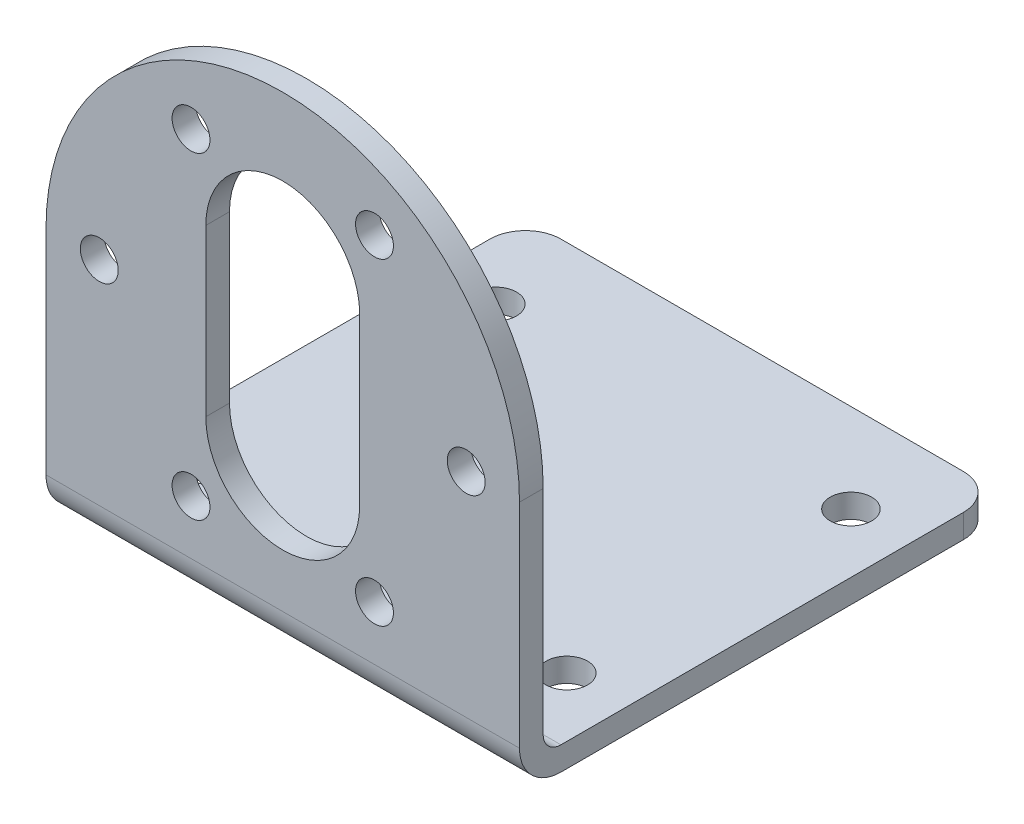
SolidWorks part; units mm, degrees
ref_plane "前视基准面" through (0, 0, 0) normal (0, 0, 1) x (1, 0, 0)
ref_plane "上视基准面" through (0, 0, 0) normal (0, 1, 0) x (1, 0, 0)
ref_plane "右视基准面" through (0, 0, 0) normal (1, 0, 0) x (0, 0, -1)
other "Configuration Table"
ref_plane "基准面1" through (0, 0, 20.25) normal (0, 0, 1) x (1, 0, 0)
sketch "草图1" plane through (0, 0, 20.25) normal (0, 0, 1) x (1, 0, 0)
  line L0 (20, -2) -> (20, 19.5)
  line L1 (-20, 19.5) -> (-20, -2)
  line L2 (-20, -2) -> (20, -2)
  arc A0 (20, 19.5) -> (-20, 19.5) centre (0, 19.5) ccw
extrude "凸台-拉伸1" add sketch "草图1" against normal blind 40.5
sketch "草图2" plane through (20, 0, 0) normal (1, 0, 0) x (0, 0, -1)
  line L0 (20.25, 19.5) -> (-18.25, 19.5)
  line L1 (-18.25, 19.5) -> (-18.25, 0)
  line L2 (-18.25, 0) -> (20.25, 0)
  line L3 (20.25, 0) -> (20.25, 19.5)
extrude "切除-拉伸1" cut sketch "草图2" against normal through all
sketch "草图3" plane through (0, 0, 20.25) normal (0, 0, 1) x (1, 0, 0)
  line L0 (-6.5, 26.5) -> (-6.5, 12.5)
  line L1 (6.5, 12.5) -> (6.5, 26.5)
  arc A0 (6.5, 26.5) -> (-6.5, 26.5) centre (0, 26.5) ccw
  arc A1 (-6.5, 12.5) -> (6.5, 12.5) centre (0, 12.5) ccw
extrude "切除-拉伸2" cut sketch "草图3" against normal blind 2
hole_wizard "Ø3.5 (3.5) 直径孔1" positions "草图5" profile "草图4" hole size "Ø3.5" standard "ANSI Metric"
sketch "草图5" plane through (0, -2, 0) normal (0, -1, 0) x (-1, 0, 0)
  point P0 (15, -11.25)
  point P1 (15, 12.75)
  point P2 (-15, 12.75)
  point P3 (-15, -11.25)
sketch "草图4" plane through (-15, -2, 11.25) normal (1, 0, 0) x (0, 0, -1)
  line L0 (0, 0) -> (0, 2)
  line L1 (0, 2) -> (1.75, 2)
  line L2 (1.75, 2) -> (1.75, 0)
  line L5 (1.75, 0) -> (0, 0)
  line L11 (0, -6.35) -> (0, 107.95) construction
  dimension "通孔孔直径" = 3.5
  dimension "通孔孔深度" = 2
hole_wizard "Ø3.2 (3.2) 直径孔1" positions "草图7" profile "草图6" hole size "Ø3.2" standard "ANSI Metric"
sketch "草图7" plane through (0, 0, 20.25) normal (0, 0, 1) x (1, 0, 0)
  point P0 (-7.75, 32.9234)
  point P1 (-7.75, 6.0766)
  point P2 (15.5, 19.5)
  point P3 (7.75, 6.0766)
  point P4 (-15.5, 19.5)
  point P5 (7.75, 32.9234)
sketch "草图6" plane through (-7.75, 32.9234, 20.25) normal (1, 0, 0) x (0, -1, 0)
  line L0 (0, 0) -> (0, 40.5)
  line L1 (0, 40.5) -> (1.6, 40.5)
  line L2 (1.6, 40.5) -> (1.6, 0)
  line L5 (1.6, 0) -> (0, 0)
  line L11 (0, -6.35) -> (0, 107.95) construction
  dimension "通孔孔直径" = 3.2
  dimension "通孔孔深度" = 40.5
fillet "圆角1" radius 1.5 1 edges at (0, 0, 18.25)
fillet "圆角2" radius 3 2 edges at (20, -1, -20.25) (-20, -1, -20.25)
fillet "圆角3" radius 3.5 1 edges at (0, -2, 20.25)
sketch "草图12" plane through (0, 0, -20.25) normal (0, 0, -1) x (-1, 0, 0)
  line L0 (20, 19.5) -> (17.1, 19.5) construction
  line L1 (-17.1, 19.5) -> (-20, 19.5) construction
  line L2 (-20, 19.5) -> (-17.1, 19.5)
  line L3 (-13.9, 19.5) -> (13.9, 19.5)
  line L4 (17.1, 19.5) -> (20, 19.5)
  arc A0 (-13.9, 19.5) -> (-17.1, 19.5) centre (-15.5, 19.5) ccw
  arc A1 (-13.9, 19.5) -> (-17.1, 19.5) centre (-15.5, 19.5) ccw construction
  arc A2 (17.1, 19.5) -> (13.9, 19.5) centre (15.5, 19.5) ccw
  arc A3 (17.1, 19.5) -> (13.9, 19.5) centre (15.5, 19.5) ccw construction
  arc A4 (20, 19.5) -> (-20, 19.5) centre (0, 19.5) ccw
  circle A5 centre (-7.75, 32.9234) radius 1.6
  circle A6 centre (7.75, 32.9234) radius 1.6
  arc A7 (20, 19.5) -> (-20, 19.5) centre (0, 19.5) ccw construction
extrude "切除-拉伸3" cut sketch "草图12" against normal blind 38.5
